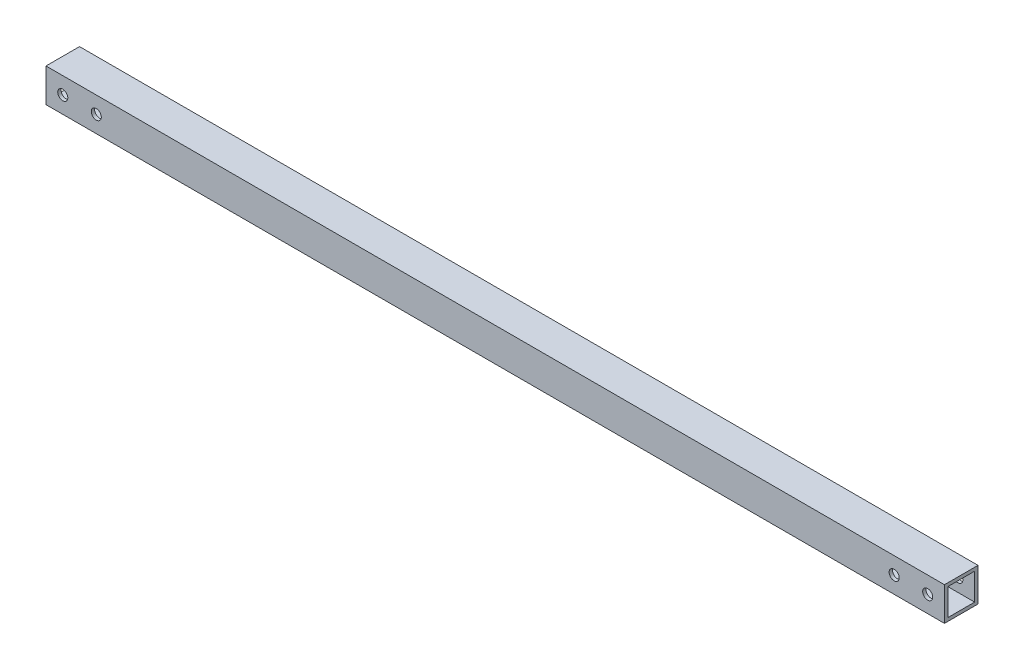
SolidWorks part; units mm, degrees
material "1060 Alloy"
ref_plane "Front Plane" through (0, 0, 0) normal (0, 0, 1) x (1, 0, 0)
ref_plane "Top Plane" through (0, 0, 0) normal (0, 1, 0) x (1, 0, 0)
ref_plane "Right Plane" through (0, 0, 0) normal (1, 0, 0) x (0, 0, -1)
sketch "Sketch1" plane through (0, 0, 0) normal (1, 0, 0) x (0, 0, -1)
  line L0 (8, 8) -> (-8, 8)
  line L1 (-8, 8) -> (-8, -8)
  line L2 (0, 0) -> (0, 27.1676) construction
  line L3 (0, 0) -> (-28.5263, 0) construction
  line L4 (8, 8) -> (8, -8)
  line L5 (8, -8) -> (-8, -8)
  line L7 (-10, 10) -> (10, 10)
  line L8 (-10, 10) -> (-10, -10)
  line L9 (-10, -10) -> (10, -10)
  line L10 (10, 10) -> (10, -10)
  point P8 (0, 8)
  point P11 (8, 0)
  point P12 (-8, 0)
  dimension "D1" = 16
  dimension "D2" = 20
  dimension "D3" = 10
  dimension "D4" = 10
extrude "Boss-Extrude1" add sketch "Sketch1" along normal mid plane 536
sketch "Sketch2" plane through (0, 0, 10) normal (0, 0, 1) x (1, 0, 0)
  line L0 (0, 0) -> (333.0514, 0) construction
  line L1 (268, 10) -> (268, -10) construction
  line L2 (-268, 10) -> (-268, -10) construction
  circle A0 centre (258, 0) radius 3
  circle A1 centre (238, 0) radius 3
  circle A2 centre (-238, 0) radius 3
  circle A3 centre (-258, 0) radius 3
  dimension "D1" = 6
  dimension "D2" = 20
  dimension "D3" = 10
  dimension "D4" = 20
  dimension "D5" = 10
extrude "Cut-Extrude1" cut sketch "Sketch2" against normal through all
